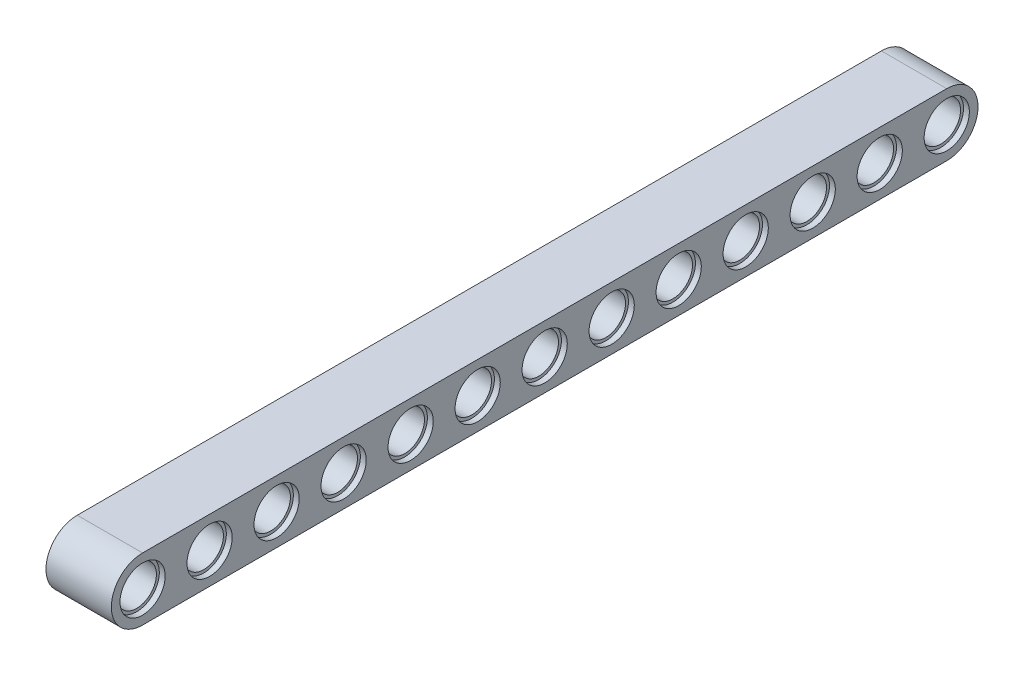
SolidWorks part; units mm, degrees
ref_plane "Front Plane" through (0, 0, 0) normal (0, 0, 1) x (1, 0, 0)
ref_plane "Top Plane" through (0, 0, 0) normal (0, 1, 0) x (1, 0, 0)
ref_plane "Right Plane" through (0, 0, 0) normal (1, 0, 0) x (0, 0, -1)
sketch "Sketch1" plane through (0, 0, 0) normal (1, 0, 0) x (0, 0, -1)
  line L0 (-48, 0) -> (48, 0) construction
  line L1 (-48, 3.73) -> (48, 3.73) construction
  line L2 (-48, 3.73) -> (-48, -3.73) construction
  line L3 (-48, -3.73) -> (48, -3.73) construction
  line L4 (48, 3.73) -> (48, -3.73) construction
  line L5 (-48, 3.73) -> (48, -3.73) construction
  line L6 (-48, -3.73) -> (48, 3.73) construction
  line L8 (-48, -3.73) -> (48, -3.73)
  line L10 (-48, 3.73) -> (48, 3.73)
  line L12 (-48, -3.73) -> (48, 3.73) construction
  line L13 (-48, 3.73) -> (48, -3.73) construction
  circle A0 centre (-48, 0) radius 2.35
  circle A1 centre (-40, 0) radius 2.35
  circle A2 centre (-32, 0) radius 2.35
  circle A3 centre (-24, 0) radius 2.35
  circle A4 centre (-16, 0) radius 2.35
  circle A5 centre (-8, 0) radius 2.35
  circle A6 centre (0, 0) radius 2.35
  circle A7 centre (8, 0) radius 2.35
  circle A8 centre (16, 0) radius 2.35
  circle A9 centre (24, 0) radius 2.35
  circle A10 centre (32, 0) radius 2.35
  circle A11 centre (40, 0) radius 2.35
  arc A12 (-48, 3.73) -> (-48, -3.73) centre (-48, 0) ccw
  arc A13 (48, -3.73) -> (48, 3.73) centre (48, 0) ccw
  circle A14 centre (48, 0) radius 2.35
  point P0 (0, 0)
  point P9 (0, 0)
  dimension "D3" = 4.7
  dimension "D5" = 8
  dimension "D6" = 4.7
  dimension "D1" = 96
  dimension "D2" = 7.46
  dimension "D4" = 12
extrude "Boss-Extrude1" add sketch "Sketch1" along normal blind 7.8
sketch "Sketch2" plane through (7.8, 0, 0) normal (1, 0, 0) x (0, 0, -1)
  circle A0 centre (-48, 0) radius 2.7
  circle A1 centre (-40, 0) radius 2.7
  circle A2 centre (-32, 0) radius 2.7
  circle A3 centre (-24, 0) radius 2.7
  circle A4 centre (-16, 0) radius 2.7
  circle A5 centre (-8, 0) radius 2.7
  circle A6 centre (0, 0) radius 2.7
  circle A7 centre (8, 0) radius 2.7
  circle A8 centre (16, 0) radius 2.7
  circle A9 centre (24, 0) radius 2.7
  circle A10 centre (32, 0) radius 2.7
  circle A11 centre (40, 0) radius 2.7
  circle A12 centre (48, 0) radius 2.7
  point P3 (0, 0)
  point P28 (0, 0)
  point P29 (0, 0)
  point P30 (0, 0)
  point P31 (0, 0)
  point P32 (0, 0)
  point P33 (0, 0)
  point P34 (0, 0)
  dimension "D1" = 5.4
  dimension "D2" = 13
  dimension "D3" = 8
extrude "Cut-Extrude1" cut sketch "Sketch2" against normal blind 0.7
sketch "Sketch3" plane through (0, 0, 0) normal (-1, 0, 0) x (0, 0, 1)
  line L0 (-48, 0) -> (-40, 0) construction
  circle A0 centre (-48, 0) radius 2.705
  circle A2 centre (-40, 0) radius 2.705
  circle A3 centre (-32, 0) radius 2.705
  circle A4 centre (-24, 0) radius 2.705
  circle A5 centre (-16, 0) radius 2.705
  circle A6 centre (-8, 0) radius 2.705
  circle A7 centre (0, 0) radius 2.705
  circle A8 centre (8, 0) radius 2.705
  circle A9 centre (16, 0) radius 2.705
  circle A10 centre (24, 0) radius 2.705
  circle A11 centre (32, 0) radius 2.705
  circle A12 centre (40, 0) radius 2.705
  circle A13 centre (48, 0) radius 2.705
  point P3 (0, 0)
  dimension "D1" = 5.41
  dimension "D3" = 8
  dimension "D2" = 13
extrude "Cut-Extrude2" cut sketch "Sketch3" against normal blind 0.7
